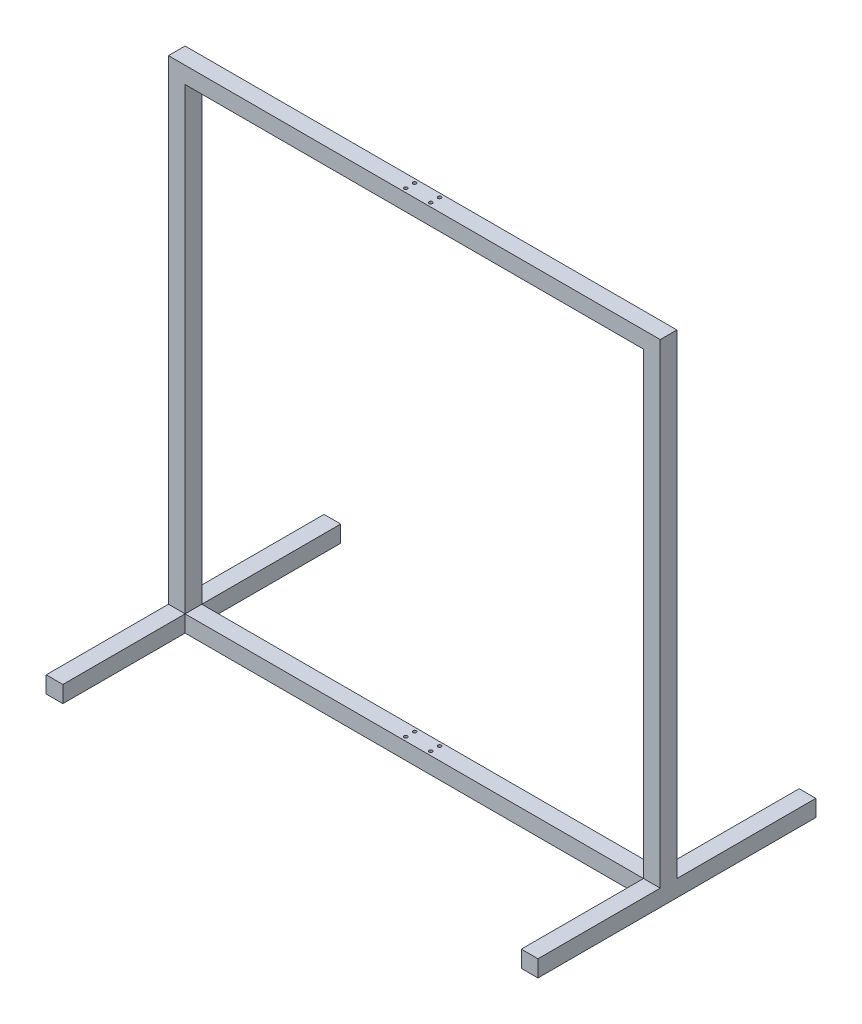
SolidWorks part; units mm, degrees
ref_plane "Front Plane" through (0, 0, 0) normal (0, 0, 1) x (1, 0, 0)
ref_plane "Top Plane" through (0, 0, 0) normal (0, 1, 0) x (1, 0, 0)
ref_plane "Right Plane" through (0, 0, 0) normal (1, 0, 0) x (0, 0, -1)
sketch "Sketch1" plane through (0, 0, 0) normal (0, 0, 1) x (1, 0, 0)
  line L0 (885, 885) -> (885, -885)
  line L1 (-825, 825) -> (825, 825)
  line L2 (-825, 825) -> (-825, -825)
  line L4 (825, 825) -> (825, -825)
  line L5 (-825, 825) -> (825, -825) construction
  line L6 (-825, -825) -> (825, 825) construction
  line L7 (-885, -885) -> (-825, -885)
  line L8 (-885, 885) -> (-885, -885)
  line L9 (-885, 885) -> (885, 885)
  line L10 (-825, -825) -> (-825, -885)
  line L11 (825, -825) -> (825, -885)
  line L12 (825, -885) -> (885, -885)
  line L14 (-885, -885) -> (885, -885) construction
  line L15 (-825, -825) -> (825, -825) construction
  point P0 (0, 0)
  dimension "D1" = 1650
  dimension "D2" = 1650
  dimension "D3" = 60
extrude "Boss-Extrude2" add sketch "Sketch1" along normal blind 60
sketch "Sketch2" plane through (0, 0, 0) normal (0, 0, 1) x (1, 0, 0)
  line L0 (-885, -825) -> (-825, -825)
  line L1 (-885, 885) -> (-885, -885) construction
  line L2 (-825, -885) -> (-825, 825) construction
  line L3 (-885, -825) -> (-885, -885)
  line L4 (-885, -885) -> (-825, -885)
  line L5 (-825, -885) -> (-825, -825)
  line L6 (825, -825) -> (885, -825)
  line L7 (825, 825) -> (825, -885) construction
  line L8 (885, -885) -> (885, 885) construction
  line L9 (885, -825) -> (885, -885)
  line L10 (885, -885) -> (825, -885)
  line L11 (825, -885) -> (825, -825)
  dimension "D1" = 60
extrude "Boss-Extrude3" add sketch "Sketch2" along normal mid plane 1000
sketch "Sketch4" plane through (-825, 0, 0) normal (1, 0, 0) x (0, 0, -1)
  line L0 (-60, -825) -> (-60, -885)
  line L1 (-500, -885) -> (500, -885) construction
  line L2 (-60, -885) -> (0, -885)
  line L3 (0, -885) -> (0, -825)
  line L4 (0, -825) -> (-60, -825)
extrude "Boss-Extrude4" add sketch "Sketch4" along normal blind 1703
sketch "Sketch5" plane through (0, 825, 0) normal (0, -1, 0) x (1, 0, 0)
  line L0 (0, 0) -> (0, 60) construction
  line L1 (-825, 0) -> (825, 0) construction
  line L2 (-825, 60) -> (825, 60) construction
  line L3 (825, 30) -> (-825, 30) construction
  line L4 (825, 60) -> (825, 0) construction
  line L5 (-825, 60) -> (-825, 0) construction
  circle A0 centre (-45, 46) radius 6
  circle A1 centre (-45, 14) radius 6
  circle A2 centre (45, 46) radius 6
  circle A3 centre (45, 14) radius 6
  dimension "D1" = 12
  dimension "D2" = 12
  dimension "D3" = 12
  dimension "D4" = 12
  dimension "D5" = 45
  dimension "D6" = 45
  dimension "D7" = 45
  dimension "D8" = 14
  dimension "D9" = 14
  dimension "D10" = 14
  dimension "D11" = 14
extrude "Cut-Extrude2" cut sketch "Sketch5" against normal blind 298 and the other way through all
